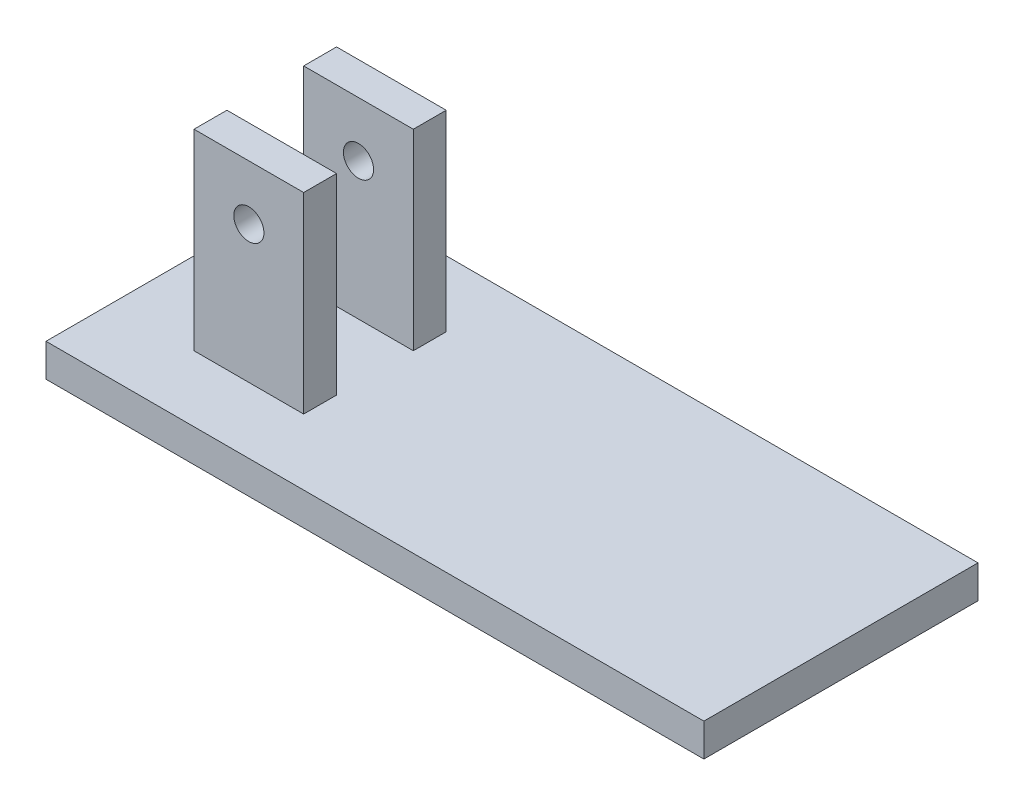
SolidWorks part; units mm, degrees
ref_plane "Front Plane" through (0, 0, 0) normal (0, 0, 1) x (1, 0, 0)
ref_plane "Top Plane" through (0, 0, 0) normal (0, 1, 0) x (1, 0, 0)
ref_plane "Right Plane" through (0, 0, 0) normal (1, 0, 0) x (0, 0, -1)
sketch "Sketch1" plane through (0, 0, 0) normal (0, 1, 0) x (1, 0, 0)
  line L1 (-60, -25) -> (60, -25)
  line L2 (-60, -25) -> (-60, 25)
  line L3 (-60, 25) -> (60, 25)
  line L4 (60, -25) -> (60, 25)
  line L5 (-60, -25) -> (60, 25) construction
  line L6 (-60, 25) -> (60, -25) construction
  point P0 (0, 0)
  dimension "D1" = 120
  dimension "D2" = 50
extrude "Boss-Extrude1" add sketch "Sketch1" along normal blind 6
sketch "Sketch2" plane through (0, 6, 0) normal (0, 1, 0) x (1, 0, 0)
  line L0 (-60, 25) -> (-60, -25) construction
  line L1 (-45, -13) -> (-25, -13)
  line L2 (-45, -13) -> (-45, -7)
  line L3 (-45, -7) -> (-25, -7)
  line L4 (-25, -13) -> (-25, -7)
  line L5 (-60, -25) -> (60, -25) construction
  dimension "D1" = 20
  dimension "D2" = 6
  dimension "D3" = 15
  dimension "D4" = 12
extrude "Boss-Extrude2" add sketch "Sketch2" along normal blind 35
sketch "Sketch3" plane through (0, 6, 0) normal (0, 1, 0) x (1, 0, 0)
  line L1 (-45, 13) -> (-25, 13)
  line L2 (-45, 13) -> (-45, 7)
  line L3 (-45, 7) -> (-25, 7)
  line L4 (-25, 13) -> (-25, 7)
  line L5 (-60, -25) -> (60, -25) construction
  line L6 (-60, 25) -> (-60, -25) construction
  dimension "D1" = 20
  dimension "D2" = 6
  dimension "D3" = 32
  dimension "D4" = 15
extrude "Boss-Extrude3" add sketch "Sketch3" along normal blind 35
sketch "Sketch4" plane through (0, 0, 13) normal (0, 0, 1) x (1, 0, 0)
  line L0 (-25, 41) -> (-25, 6) construction
  line L1 (-45, 41) -> (-25, 41) construction
  circle A0 centre (-35, 31) radius 2.75
  dimension "D1" = 5.5
  dimension "D2" = 10
  dimension "D3" = 10
extrude "Cut-Extrude1" cut sketch "Sketch4" against normal through all both and the other way through all
